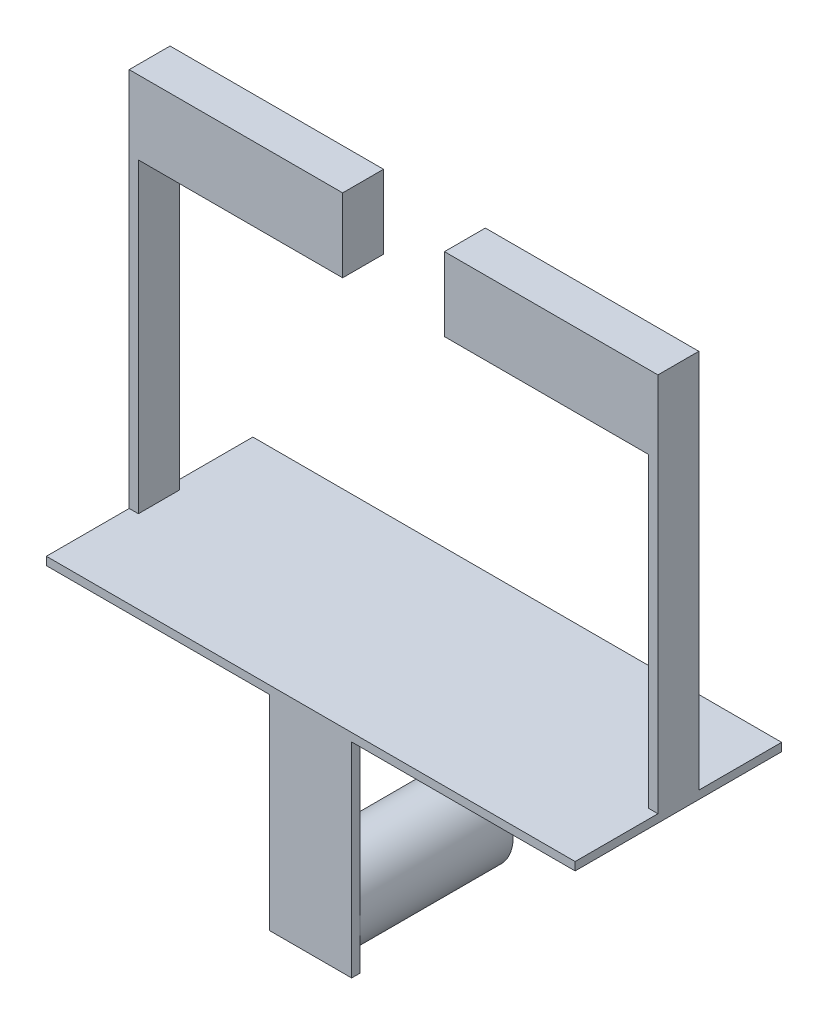
SolidWorks part; units mm, degrees
material "Ti-6Al-4V"
ref_plane "Front Plane" through (0, 0, 0) normal (0, 0, 1) x (1, 0, 0)
ref_plane "Top Plane" through (0, 0, 0) normal (0, 1, 0) x (1, 0, 0)
ref_plane "Right Plane" through (0, 0, 0) normal (1, 0, 0) x (0, 0, -1)
sketch "Sketch6" plane through (0, 0, 0) normal (0, 1, 0) x (1, 0, 0)
  line L1 (-17.2688, 8.648) -> (-7.0707, 8.648)
  line L2 (-17.2688, 8.648) -> (-17.2688, 7.632)
  line L3 (-17.2688, 7.632) -> (-7.0707, 7.632)
  line L4 (-7.0707, 8.648) -> (-7.0707, 7.632)
  dimension "D1" = 10.1981
  dimension "D2" = 1.016
extrude "Boss-Extrude3" add sketch "Sketch6" along normal blind 25.4
sketch "Sketch8" plane through (0, 0, -8.648) normal (0, 0, 1) x (1, 0, 0)
  line L1 (-7.0707, 0) -> (-17.2688, 0) construction
  line L6 (-17.2688, 10.1971) -> (-7.0707, 0) construction
  line L7 (-7.0707, 25.4) -> (-7.0707, 0) construction
  line L8 (-7.0707, 10.1971) -> (-17.2688, 10.1971) construction
  line L9 (-17.2688, 25.4) -> (-17.2688, 0) construction
  line L10 (-7.0707, 0) -> (-7.0707, 10.1971) construction
  line L11 (-7.0707, 10.1971) -> (-17.2688, 0) construction
  circle A0 centre (-12.1698, 5.0985) radius 5.0991
  dimension "D1" = 10.1981
extrude "Boss-Extrude5" add sketch "Sketch8" against normal blind 19.05
sketch "Sketch11" plane through (0, 25.4, 0) normal (0, 1, 0) x (1, 0, 0)
  line L0 (-17.2688, 7.632) -> (-7.0707, 7.632) construction
  line L3 (-44.998, 7.632) -> (20.6965, 7.632)
  line L4 (-44.998, 7.632) -> (-44.998, 33.286)
  line L5 (-44.998, 33.286) -> (20.6965, 33.286)
  line L6 (20.6965, 7.632) -> (20.6965, 33.286)
  dimension "D1" = 25.654
  dimension "D2" = 65.6946
extrude "Boss-Extrude10" add sketch "Sketch11" along normal blind 1.016
sketch "Sketch16" plane through (0, 26.416, 0) normal (0, 1, 0) x (1, 0, 0)
  line L3 (20.6965, 33.286) -> (20.6965, 7.632) construction
  line L4 (-44.998, 17.919) -> (-43.855, 17.919)
  line L7 (-44.998, 17.919) -> (-44.998, 22.999)
  line L8 (-44.998, 22.999) -> (-43.855, 22.999)
  line L9 (-43.855, 17.919) -> (-43.855, 22.999)
  line L10 (-44.998, 7.632) -> (20.6965, 7.632) construction
  line L11 (20.6965, 7.632) -> (20.6965, 33.286) construction
  line L13 (20.6965, 22.999) -> (19.5415, 22.999)
  line L14 (20.6965, 22.999) -> (20.6965, 17.919)
  line L15 (20.6965, 17.919) -> (19.5415, 17.919)
  line L16 (19.5415, 22.999) -> (19.5415, 17.919)
  dimension "D1" = 1.143
  dimension "D2" = 1.1551
  dimension "D3" = 5.08
  dimension "D4" = 5.08
extrude "Boss-Extrude11" add sketch "Sketch16" along normal blind 38.0746
sketch "Sketch17" plane through (0, 64.4906, 0) normal (0, 1, 0) x (1, 0, 0)
  line L0 (-44.998, 22.999) -> (-18.4753, 22.999) construction
  line L1 (-44.998, 17.919) -> (-41.8446, 17.919) construction
  line L2 (20.6965, 22.999) -> (-5.8261, 22.999) construction
  line L3 (-44.998, 22.999) -> (-18.4753, 22.999)
  line L4 (-44.998, 22.999) -> (-44.998, 17.919)
  line L5 (-44.998, 17.919) -> (-18.4753, 17.919)
  line L6 (-18.4753, 22.999) -> (-18.4753, 17.919)
  line L7 (20.6965, 17.919) -> (3.53, 17.919) construction
  line L9 (20.6965, 17.919) -> (-5.8261, 17.919)
  line L10 (20.6965, 17.919) -> (20.6965, 22.999)
  line L11 (20.6965, 22.999) -> (-5.8261, 22.999)
  line L12 (-5.8261, 17.919) -> (-5.8261, 22.999)
  dimension "D1" = 26.5227
  dimension "D2" = 26.5227
extrude "Boss-Extrude12" add sketch "Sketch17" along normal blind 9.144
equation "\"baseH\"= 2.5864"
equation "\"baseD\"= 1.01"
equation "\"baseT\"= 0.0422"
equation "\"cylwallH\"= 1"
equation "\"cylwallD\"= 0.4015"
equation "\"cylwallT\"= 0.0422"
equation "\"cylH\"= 1'C"
equation "\"cylD\"= 0.40146"
equation "\"cylT\"= 0.75"
equation "\"sidewallH\"= 0.045"
equation "\"sidewallD\"= 0.2"
equation "\"sidewallT\"= 1.499"
equation "\"horizwallH\"= 0.9992"
equation "\"horizwallD\"= 0.2"
equation "\"horizwallT\"= 0.356"
equation "\"E\" = 16534303"
equation "\"SF\" = 4"
equation "\"W\" = 4 * \"lbs\""
equation "\"Ys\"= 119946"
equation "\"dMAX\"= 0.005"
equation "\"lbs\"= 508"
equation "\"z\"= \"SF\" * \"W\" * ( \"cylT\" / 2 * \"Ys\" )"
equation "\"r\"= ( 4 * ( \"z\" / pi ) ) ^ ( 1 / 3 )"
